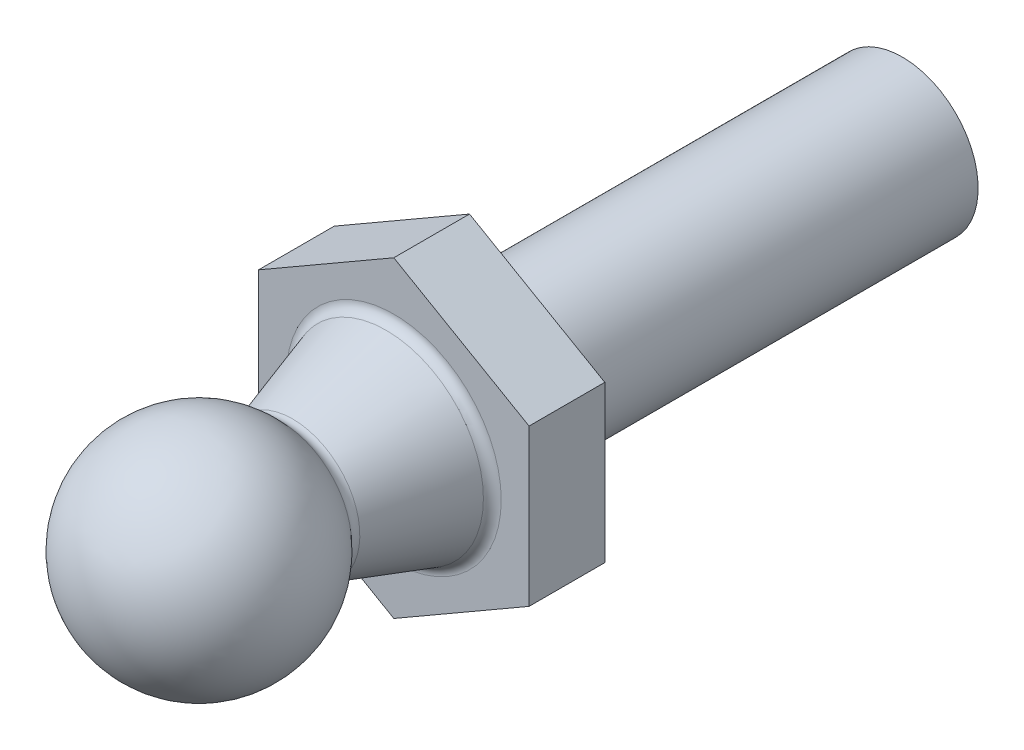
SolidWorks part; units mm, degrees
ref_plane "Front Plane" through (0, 0, 0) normal (0, 0, 1) x (1, 0, 0)
ref_plane "Top Plane" through (0, 0, 0) normal (0, 1, 0) x (1, 0, 0)
ref_plane "Right Plane" through (0, 0, 0) normal (1, 0, 0) x (0, 0, -1)
sketch "Sketch2" plane through (0, 0, 0) normal (0, 0, 1) x (1, 0, 0)
  line L1 (0, 7.2169) -> (-6.25, 3.6084)
  line L2 (-6.25, 3.6084) -> (-6.25, -3.6084)
  line L3 (-6.25, -3.6084) -> (0, -7.2169)
  line L4 (0, -7.2169) -> (6.25, -3.6084)
  line L5 (6.25, -3.6084) -> (6.25, 3.6084)
  line L6 (6.25, 3.6084) -> (0, 7.2169)
  circle A0 centre (0, 0) radius 6.25 construction
  dimension "D1" = 12.5
extrude "Boss-Extrude2" add sketch "Sketch2" along normal blind 3.5
sketch "Sketch3" plane through (0, 0, 0) normal (0, 0, -1) x (-1, 0, 0)
  circle A0 centre (0, 0) radius 3.5
  dimension "D1" = 7
extrude "Boss-Extrude3" add sketch "Sketch3" along normal blind 20
sketch "Sketch4" plane through (0, 0, 0) normal (1, 0, 0) x (0, 0, -1)
  line L1 (-3.5, -3.6084) -> (-3.5, 3.6084) construction
  line L4 (-3.5, 0) -> (-17.5, 0)
  line L5 (-3.5, 0) -> (-3.5, 4.6)
  line L6 (-3.5, 3.6084) -> (-3.5, 7.2169) construction
  line L7 (-3.5, 4.6) -> (-8.5, 3)
  line L8 (-17.5, 0) -> (-17.5, -0.2444) construction
  arc A1 (-17.5, 0) -> (-8.5, 3) centre (-12.5, 0) cw
  dimension "D4" = 3
  dimension "D2" = 5
  dimension "D1" = 4.6
  dimension "D3" = 5
revolve "Revolve1" add sketch "Sketch4" angle 360 about L4
fillet "Fillet1" radius 0.5 2 edges at (0, 3, 8.5) (0, 4.6, 3.5)
